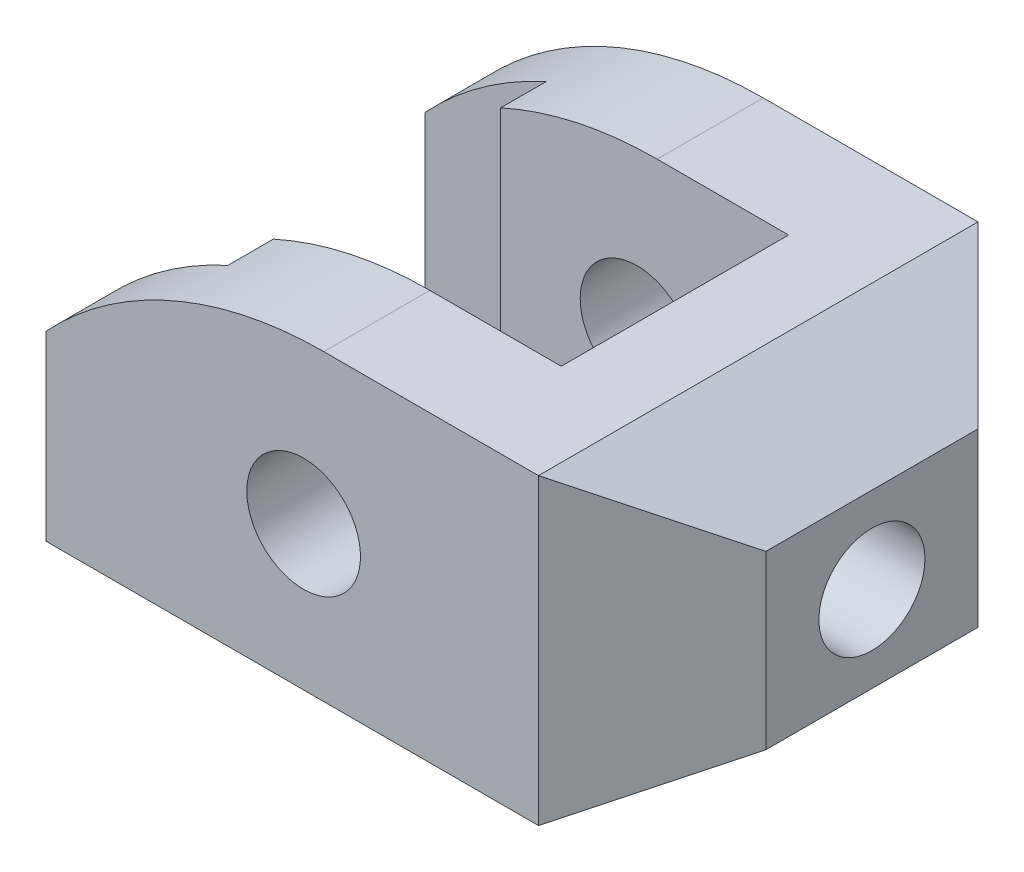
SolidWorks part; units mm, degrees
material "1060 Alloy"
ref_plane "Front Plane" through (0, 0, 0) normal (0, 0, 1) x (1, 0, 0)
ref_plane "Top Plane" through (0, 0, 0) normal (0, 1, 0) x (1, 0, 0)
ref_plane "Right Plane" through (0, 0, 0) normal (1, 0, 0) x (0, 0, -1)
sketch "Sketch1" plane through (0, 0, 0) normal (0, 0, 1) x (1, 0, 0)
  line L0 (0, 0) -> (65, 0)
  line L1 (65, 0) -> (80, 8.6603)
  line L2 (80, 8.6603) -> (80, 31.3397)
  line L3 (80, 31.3397) -> (65, 40)
  line L4 (65, 40) -> (36.6606, 40)
  line L5 (0, 0) -> (0, 24)
  arc A0 (36.6606, 40) -> (0, 24) centre (36.6606, -10) ccw
  circle A1 centre (34, 19) radius 7.5
  dimension "D8" = 50
  dimension "D9" = 15
  dimension "D10" = 19
  dimension "D1" = 65
  dimension "D2" = 40
  dimension "D3" = 15
  dimension "D4" = 15
  dimension "D5" = 30
  dimension "D6" = 30
  dimension "D7" = 24
  dimension "D11" = 31
extrude "Boss-Extrude1" add sketch "Sketch1" along normal mid plane 58
sketch "Sketch2" plane through (0, 0, 0) normal (0, 1, 0) x (1, 0, 0)
  line L0 (0, -29) -> (0, 29) construction
  line L1 (0, 21) -> (16, 21)
  line L2 (0, 21) -> (0, -21)
  line L3 (0, -21) -> (16, -21)
  line L4 (16, 21) -> (16, 15)
  line L5 (36.6606, -29) -> (36.6606, 29) construction
  line L6 (16, 15) -> (54, 15)
  line L8 (16, -15) -> (54, -15)
  line L9 (54, 15) -> (54, -15)
  line L10 (16, -15) -> (16, -21)
  line L12 (36.6606, 29) -> (0, 29) construction
  line L13 (0, -29) -> (36.6606, -29) construction
  line L14 (65, -29) -> (65, 29) construction
  point P6 (36.6606, 0)
  dimension "D1" = 8
  dimension "D2" = 8
  dimension "D3" = 11
  dimension "D4" = 30
  dimension "D5" = 6
  dimension "D6" = 16
extrude "Cut-Extrude1" cut sketch "Sketch2" along normal blind 58
sketch "Sketch3" plane through (0, 0, 0) normal (0, 1, 0) x (1, 0, 0)
  line L0 (80, 29) -> (65, 29)
  line L1 (65, 29) -> (80, 14)
  line L2 (80, -29) -> (80, 29) construction
  line L3 (80, -29) -> (65, -29)
  line L4 (65, -29) -> (80, -14)
  line L5 (65, 29) -> (36.6606, 29) construction
  line L7 (65, -29) -> (36.6606, -29) construction
  line L8 (80, -29) -> (80, -14)
  line L9 (80, 14) -> (80, 29)
  dimension "D1" = 45
  dimension "D2" = 45
extrude "Cut-Extrude2" cut sketch "Sketch3" along normal blind 58
sketch "Sketch7" plane through (80, 0, 0) normal (1, 0, 0) x (0, 0, -1)
  line L1 (-29, 40) -> (-29, 0) construction
  line L2 (-29, 0) -> (29, 0) construction
  circle A0 centre (0, 20) radius 7
  dimension "D1" = 14
  dimension "D2" = 29
  dimension "D3" = 20
extrude "Cut-Extrude3" cut sketch "Sketch7" against normal blind 58
equation "\"A\"= 58mm"
equation "\"B\"= 40mm"
equation "\"C\"= 65mm"
